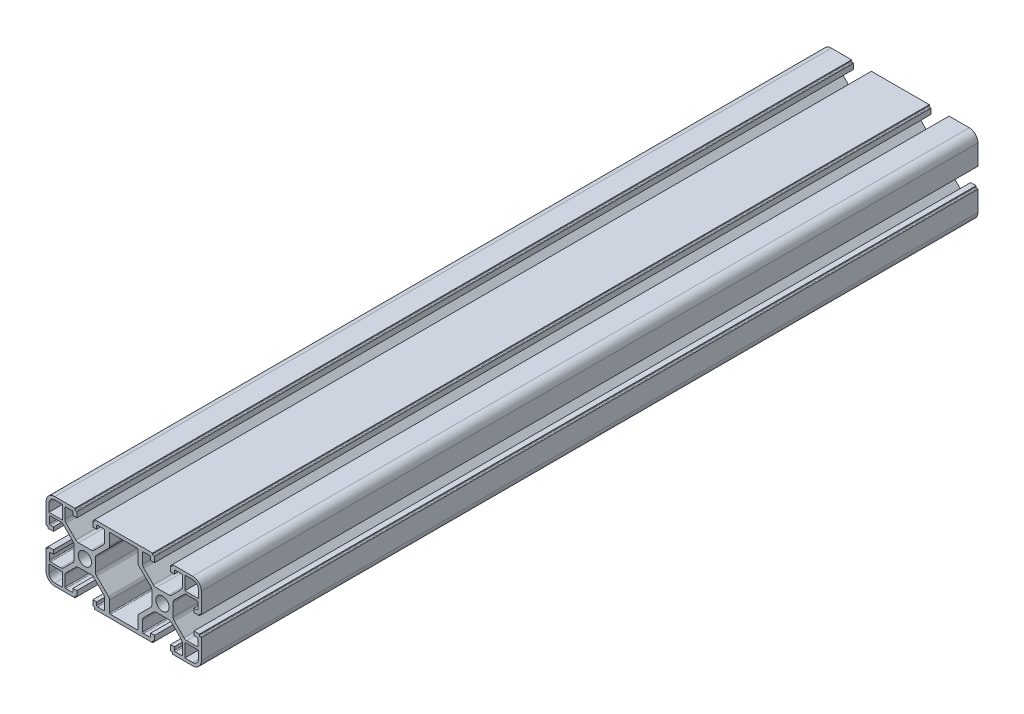
SolidWorks part; units mm, degrees
material "1060 合金"
ref_plane "前视基准面" through (0, 0, 0) normal (0, 0, 1) x (1, 0, 0)
ref_plane "上视基准面" through (0, 0, 0) normal (0, 1, 0) x (1, 0, 0)
ref_plane "右视基准面" through (0, 0, 0) normal (1, 0, 0) x (0, 0, -1)
sketch "草图1" plane through (0, 0, 0) normal (0, 0, 1) x (1, 0, 0)
  line L0 (-18.5, 15.5) -> (-18.5, 11.5)
  line L1 (-3.2574, 5.5) -> (3.2574, 5.5)
  line L2 (-5.5, 3.2574) -> (-5.5, -3.2574)
  line L3 (-3.2574, -5.5) -> (3.2574, -5.5)
  line L4 (5.5, 3.2574) -> (5.5, -3.2574)
  line L5 (-5.5, 5.5) -> (5.5, -5.5) construction
  line L6 (-5.5, -5.5) -> (5.5, 5.5) construction
  line L7 (-15.5, 20) -> (-5.1, 20)
  line L8 (-20, 15.5) -> (-20, 5.1)
  line L9 (-15.5, -20) -> (-5.1, -20)
  line L10 (60, 15.5) -> (60, 5.1)
  line L11 (36.7426, 5.5) -> (43.2574, 5.5)
  line L12 (34.5, 3.2574) -> (34.5, -3.2574)
  line L13 (36.7426, -5.5) -> (43.2574, -5.5)
  line L14 (45.5, 3.2574) -> (45.5, -3.2574)
  line L15 (34.5, 5.5) -> (45.5, -5.5) construction
  line L16 (34.5, -5.5) -> (45.5, 5.5) construction
  line L21 (-11.5, 18.5) -> (-15.5, 18.5)
  line L22 (-18.5, 11.5) -> (-11.5, 11.5)
  line L27 (6.0858, 4.6716) -> (12.1142, 10.7)
  line L28 (4.6716, 6.0858) -> (9.6642, 11.0784)
  line L33 (20, 42.3045) -> (20, -35.7395) construction
  line L34 (58.5, 15.5) -> (58.5, 11.5)
  line L39 (51.5, 18.5) -> (55.5, 18.5)
  line L40 (51.5, 18.5) -> (51.5, 11.5)
  line L41 (-9.6642, 11.0784) -> (-4.6716, 6.0858)
  line L47 (58.5, 11.5) -> (51.5, 11.5)
  line L48 (27.3, 17.7) -> (27.3, 12.1142)
  line L53 (33.9142, 4.6716) -> (27.8858, 10.7)
  line L54 (35.3284, 6.0858) -> (30.3358, 11.0784)
  line L58 (-10.25, 20.75) -> (-10.25, 20) construction
  line L59 (-20.25, 20.25) -> (-10.75, 10.75) construction
  line L60 (-20.25, 10.75) -> (-10.25, 20.75) construction
  line L65 (29.75, 17.7) -> (29.75, 12.4926)
  line L66 (30.25, 18.2) -> (33.4, 18.2)
  line L67 (-11.0784, 9.6642) -> (-6.0858, 4.6716)
  line L68 (33.9, 17.7) -> (33.9, 16.2)
  line L69 (33.9, 16.2) -> (35.9, 16.2)
  line L70 (34.9, 19.5) -> (34.9, 20)
  line L71 (35.9, 19) -> (35.4, 19)
  line L72 (35.9, 16.2) -> (35.9, 19)
  line L73 (51.0784, 9.6642) -> (46.0858, 4.6716)
  line L74 (52.4926, 10.25) -> (57.7, 10.25)
  line L76 (10.25, 17.7) -> (10.25, 12.4926)
  line L79 (12.7, 17.7) -> (12.7, 12.1142)
  line L81 (13.2, 18.2) -> (26.8, 18.2)
  line L83 (45.1, 19.5) -> (45.1, 20)
  line L84 (9.75, 18.2) -> (6.6, 18.2)
  line L85 (6.1, 17.7) -> (6.1, 16.2)
  line L86 (6.1, 16.2) -> (4.1, 16.2)
  line L87 (4.1, 16.2) -> (4.1, 19)
  line L88 (4.1, 19) -> (4.6, 19)
  line L89 (5.1, 19.5) -> (5.1, 20)
  line L90 (0, 23.211) -> (0, -33.1546) construction
  line L91 (-4.1, 16.2) -> (-6.1, 16.2)
  line L92 (-6.1, 16.2) -> (-6.1, 17.7)
  line L93 (-6.6, 18.2) -> (-9.75, 18.2)
  line L94 (-4.1, 16.2) -> (-4.1, 19)
  line L95 (-4.1, 19) -> (-4.656, 19)
  line L96 (-4.656, 19) -> (-4.6, 19)
  line L97 (-5.1, 19.5) -> (-5.1, 20)
  line L98 (-10.25, 17.7) -> (-10.25, 12.4926)
  line L99 (44.1, 19) -> (44.656, 19)
  line L100 (44.1, 16.2) -> (44.1, 19)
  line L101 (-11.5, 18.5) -> (-11.5, 11.5)
  line L102 (-12.4926, 10.25) -> (-17.7, 10.25)
  line L103 (44.1, 16.2) -> (46.1, 16.2)
  line L104 (46.1, 16.2) -> (46.1, 17.7)
  line L105 (46.6, 18.2) -> (49.75, 18.2)
  line L106 (50.25, 17.7) -> (50.25, 12.4926)
  line L107 (49.6642, 11.0784) -> (44.6716, 6.0858)
  line L108 (-37.1629, 0) -> (-20, 0) construction
  line L109 (-11.5, -18.5) -> (-15.5, -18.5)
  line L110 (-11.5, -18.5) -> (-11.5, -11.5)
  line L111 (-18.5, -11.5) -> (-11.5, -11.5)
  line L112 (-18.5, -15.5) -> (-18.5, -11.5)
  line L113 (-10.25, -17.7) -> (-10.25, -12.4926)
  line L114 (-12.4926, -10.25) -> (-17.7, -10.25)
  line L115 (-9.6642, -11.0784) -> (-4.6716, -6.0858)
  line L116 (-11.0784, -9.6642) -> (-6.0858, -4.6716)
  line L117 (-4.1, -16.2) -> (-4.1, -19)
  line L118 (-4.1, -16.2) -> (-6.1, -16.2)
  line L119 (-6.1, -16.2) -> (-6.1, -17.7)
  line L120 (-6.6, -18.2) -> (-9.75, -18.2)
  line L121 (-4.1, -19) -> (-4.656, -19)
  line L122 (-5.1, -19.5) -> (-5.1, -20)
  line L123 (10.25, -17.7) -> (10.25, -12.4926)
  line L124 (12.7, -17.7) -> (12.7, -12.1142)
  line L125 (4.6716, -6.0858) -> (9.6642, -11.0784)
  line L126 (6.0858, -4.6716) -> (12.1142, -10.7)
  line L127 (13.2, -18.2) -> (26.8, -18.2)
  line L128 (5.1, -19.5) -> (5.1, -20)
  line L129 (4.1, -19) -> (4.6, -19)
  line L130 (4.1, -16.2) -> (4.1, -19)
  line L131 (6.1, -16.2) -> (4.1, -16.2)
  line L132 (6.1, -17.7) -> (6.1, -16.2)
  line L133 (9.75, -18.2) -> (6.6, -18.2)
  line L134 (35.3284, -6.0858) -> (30.3358, -11.0784)
  line L135 (34.9, -19.5) -> (34.9, -20)
  line L136 (35.9, -19) -> (35.4, -19)
  line L137 (35.9, -16.2) -> (35.9, -19)
  line L138 (33.9, -16.2) -> (35.9, -16.2)
  line L139 (33.9, -17.7) -> (33.9, -16.2)
  line L140 (30.25, -18.2) -> (33.4, -18.2)
  line L141 (29.75, -17.7) -> (29.75, -12.4926)
  line L142 (33.9142, -4.6716) -> (27.8858, -10.7)
  line L143 (27.3, -17.7) -> (27.3, -12.1142)
  line L144 (52.4926, -10.25) -> (57.7, -10.25)
  line L145 (44.1, -19) -> (44.656, -19)
  line L146 (45.1, -19.5) -> (45.1, -20)
  line L147 (44.1, -16.2) -> (44.1, -19)
  line L148 (44.1, -16.2) -> (46.1, -16.2)
  line L149 (46.1, -16.2) -> (46.1, -17.7)
  line L150 (46.6, -18.2) -> (49.75, -18.2)
  line L151 (50.25, -17.7) -> (50.25, -12.4926)
  line L152 (49.6642, -11.0784) -> (44.6716, -6.0858)
  line L153 (51.0784, -9.6642) -> (46.0858, -4.6716)
  line L154 (58.5, -15.5) -> (58.5, -11.5)
  line L155 (58.5, -11.5) -> (51.5, -11.5)
  line L156 (51.5, -18.5) -> (51.5, -11.5)
  line L157 (51.5, -18.5) -> (55.5, -18.5)
  line L158 (45.1, 20) -> (55.5, 20)
  line L159 (5.1, 20) -> (34.9, 20)
  line L160 (5.1, -20) -> (34.9, -20)
  line L161 (45.1, -20) -> (55.5, -20)
  line L162 (-16.2, 4.1) -> (-16.2, 6.1)
  line L163 (-16.2, 6.1) -> (-17.7, 6.1)
  line L164 (-18.2, 6.6) -> (-18.2, 9.75)
  line L165 (-19.5, 5.1) -> (-20, 5.1)
  line L166 (-19, 4.1) -> (-19, 4.656)
  line L167 (-16.2, 4.1) -> (-19, 4.1)
  line L168 (-18.2, -6.6) -> (-18.2, -9.75)
  line L169 (-16.2, -6.1) -> (-17.7, -6.1)
  line L170 (-16.2, -4.1) -> (-16.2, -6.1)
  line L171 (-16.2, -4.1) -> (-19, -4.1)
  line L172 (-19.5, -5.1) -> (-20, -5.1)
  line L173 (-19, -4.1) -> (-19, -4.656)
  line L174 (59.5, -5.1) -> (60, -5.1)
  line L175 (59, -4.1) -> (59, -4.656)
  line L176 (56.2, -4.1) -> (59, -4.1)
  line L177 (56.2, -4.1) -> (56.2, -6.1)
  line L178 (56.2, -6.1) -> (57.7, -6.1)
  line L179 (58.2, -6.6) -> (58.2, -9.75)
  line L180 (59.5, 5.1) -> (60, 5.1)
  line L181 (59, 4.1) -> (59, 4.656)
  line L182 (56.2, 4.1) -> (59, 4.1)
  line L183 (56.2, 4.1) -> (56.2, 6.1)
  line L184 (56.2, 6.1) -> (57.7, 6.1)
  line L185 (58.2, 6.6) -> (58.2, 9.75)
  line L186 (60, -5.1) -> (60, -15.5)
  line L187 (-20, -5.1) -> (-20, -15.5)
  line L188 (-5.5, 0) -> (60, 0) construction
  circle A0 centre (0, 0) radius 3.4
  circle A1 centre (40, 0) radius 3.4
  arc A2 (-15.5, 20) -> (-20, 15.5) centre (-15.5, 15.5) ccw
  arc A3 (60, 15.5) -> (55.5, 20) centre (55.5, 15.5) ccw
  arc A4 (55.5, -20) -> (60, -15.5) centre (55.5, -15.5) ccw
  arc A5 (-20, -15.5) -> (-15.5, -20) centre (-15.5, -15.5) ccw
  arc A10 (-15.5, 18.5) -> (-18.5, 15.5) centre (-15.5, 15.5) ccw
  arc A11 (-9.75, 18.2) -> (-10.25, 17.7) centre (-9.75, 17.7) ccw
  arc A12 (-6.1, 17.7) -> (-6.6, 18.2) centre (-6.6, 17.7) ccw
  arc A13 (-5.1, 19.5) -> (-4.6, 19) centre (-4.6, 19.5) ccw
  arc A14 (4.6, 19) -> (5.1, 19.5) centre (4.6, 19.5) ccw
  arc A15 (6.6, 18.2) -> (6.1, 17.7) centre (6.6, 17.7) ccw
  arc A16 (10.25, 17.7) -> (9.75, 18.2) centre (9.75, 17.7) ccw
  arc A17 (9.6642, 11.0784) -> (10.25, 12.4926) centre (8.25, 12.4926) ccw
  arc A18 (-10.25, 12.4926) -> (-9.6642, 11.0784) centre (-8.25, 12.4926) ccw
  arc A20 (-11.0784, 9.6642) -> (-12.4926, 10.25) centre (-12.4926, 8.25) ccw
  arc A21 (12.1142, 10.7) -> (12.7, 12.1142) centre (10.7, 12.1142) ccw
  arc A22 (-4.6716, 6.0858) -> (-3.2574, 5.5) centre (-3.2574, 7.5) ccw
  arc A23 (3.2574, 5.5) -> (4.6716, 6.0858) centre (3.2574, 7.5) ccw
  arc A24 (13.2, 18.2) -> (12.7, 17.7) centre (13.2, 17.7) ccw
  arc A25 (6.0858, 4.6716) -> (5.5, 3.2574) centre (7.5, 3.2574) ccw
  arc A26 (-5.5, 3.2574) -> (-6.0858, 4.6716) centre (-7.5, 3.2574) ccw
  arc A27 (58.5, 15.5) -> (55.5, 18.5) centre (55.5, 15.5) ccw
  arc A28 (26.8, 18.2) -> (27.3, 17.7) centre (26.8, 17.7) cw
  arc A29 (27.8858, 10.7) -> (27.3, 12.1142) centre (29.3, 12.1142) cw
  arc A30 (33.9142, 4.6716) -> (34.5, 3.2574) centre (32.5, 3.2574) cw
  arc A31 (36.7426, 5.5) -> (35.3284, 6.0858) centre (36.7426, 7.5) cw
  arc A32 (30.3358, 11.0784) -> (29.75, 12.4926) centre (31.75, 12.4926) cw
  arc A33 (29.75, 17.7) -> (30.25, 18.2) centre (30.25, 17.7) cw
  arc A34 (33.4, 18.2) -> (33.9, 17.7) centre (33.4, 17.7) cw
  arc A35 (35.4, 19) -> (34.9, 19.5) centre (35.4, 19.5) cw
  arc A36 (45.5, 3.2574) -> (46.0858, 4.6716) centre (47.5, 3.2574) cw
  arc A37 (44.6716, 6.0858) -> (43.2574, 5.5) centre (43.2574, 7.5) cw
  arc A38 (51.0784, 9.6642) -> (52.4926, 10.25) centre (52.4926, 8.25) cw
  arc A39 (45.1, 19.5) -> (44.6, 19) centre (44.6, 19.5) cw
  arc A40 (46.1, 17.7) -> (46.6, 18.2) centre (46.6, 17.7) cw
  arc A41 (49.75, 18.2) -> (50.25, 17.7) centre (49.75, 17.7) cw
  arc A42 (50.25, 12.4926) -> (49.6642, 11.0784) centre (48.25, 12.4926) cw
  arc A43 (-18.5, -15.5) -> (-15.5, -18.5) centre (-15.5, -15.5) ccw
  arc A44 (-11.0784, -9.6642) -> (-12.4926, -10.25) centre (-12.4926, -8.25) cw
  arc A45 (-10.25, -12.4926) -> (-9.6642, -11.0784) centre (-8.25, -12.4926) cw
  arc A46 (-4.6716, -6.0858) -> (-3.2574, -5.5) centre (-3.2574, -7.5) cw
  arc A47 (-5.5, -3.2574) -> (-6.0858, -4.6716) centre (-7.5, -3.2574) cw
  arc A48 (-6.1, -17.7) -> (-6.6, -18.2) centre (-6.6, -17.7) cw
  arc A49 (-9.75, -18.2) -> (-10.25, -17.7) centre (-9.75, -17.7) cw
  arc A50 (-5.1, -19.5) -> (-4.6, -19) centre (-4.6, -19.5) cw
  arc A51 (12.1142, -10.7) -> (12.7, -12.1142) centre (10.7, -12.1142) cw
  arc A52 (9.6642, -11.0784) -> (10.25, -12.4926) centre (8.25, -12.4926) cw
  arc A53 (6.0858, -4.6716) -> (5.5, -3.2574) centre (7.5, -3.2574) cw
  arc A54 (3.2574, -5.5) -> (4.6716, -6.0858) centre (3.2574, -7.5) cw
  arc A55 (4.6, -19) -> (5.1, -19.5) centre (4.6, -19.5) cw
  arc A56 (6.6, -18.2) -> (6.1, -17.7) centre (6.6, -17.7) cw
  arc A57 (13.2, -18.2) -> (12.7, -17.7) centre (13.2, -17.7) cw
  arc A58 (10.25, -17.7) -> (9.75, -18.2) centre (9.75, -17.7) cw
  arc A59 (33.9142, -4.6716) -> (34.5, -3.2574) centre (32.5, -3.2574) ccw
  arc A60 (36.7426, -5.5) -> (35.3284, -6.0858) centre (36.7426, -7.5) ccw
  arc A61 (35.4, -19) -> (34.9, -19.5) centre (35.4, -19.5) ccw
  arc A62 (33.4, -18.2) -> (33.9, -17.7) centre (33.4, -17.7) ccw
  arc A63 (29.75, -17.7) -> (30.25, -18.2) centre (30.25, -17.7) ccw
  arc A64 (30.3358, -11.0784) -> (29.75, -12.4926) centre (31.75, -12.4926) ccw
  arc A65 (27.8858, -10.7) -> (27.3, -12.1142) centre (29.3, -12.1142) ccw
  arc A66 (26.8, -18.2) -> (27.3, -17.7) centre (26.8, -17.7) ccw
  arc A67 (51.0784, -9.6642) -> (52.4926, -10.25) centre (52.4926, -8.25) ccw
  arc A68 (45.1, -19.5) -> (44.6, -19) centre (44.6, -19.5) ccw
  arc A69 (46.1, -17.7) -> (46.6, -18.2) centre (46.6, -17.7) ccw
  arc A70 (49.75, -18.2) -> (50.25, -17.7) centre (49.75, -17.7) ccw
  arc A71 (50.25, -12.4926) -> (49.6642, -11.0784) centre (48.25, -12.4926) ccw
  arc A72 (45.5, -3.2574) -> (46.0858, -4.6716) centre (47.5, -3.2574) ccw
  arc A73 (44.6716, -6.0858) -> (43.2574, -5.5) centre (43.2574, -7.5) ccw
  arc A74 (55.5, -18.5) -> (58.5, -15.5) centre (55.5, -15.5) ccw
  arc A75 (-17.7, 6.1) -> (-18.2, 6.6) centre (-17.7, 6.6) cw
  arc A76 (-18.2, 9.75) -> (-17.7, 10.25) centre (-17.7, 9.75) cw
  arc A77 (-19.5, 5.1) -> (-19, 4.6) centre (-19.5, 4.6) cw
  arc A78 (-18.2, -9.75) -> (-17.7, -10.25) centre (-17.7, -9.75) ccw
  arc A79 (-17.7, -6.1) -> (-18.2, -6.6) centre (-17.7, -6.6) ccw
  arc A80 (-19.5, -5.1) -> (-19, -4.6) centre (-19.5, -4.6) ccw
  arc A81 (59.5, -5.1) -> (59, -4.6) centre (59.5, -4.6) cw
  arc A82 (57.7, -6.1) -> (58.2, -6.6) centre (57.7, -6.6) cw
  arc A83 (58.2, -9.75) -> (57.7, -10.25) centre (57.7, -9.75) cw
  arc A84 (59.5, 5.1) -> (59, 4.6) centre (59.5, 4.6) ccw
  arc A85 (57.7, 6.1) -> (58.2, 6.6) centre (57.7, 6.6) ccw
  arc A86 (58.2, 9.75) -> (57.7, 10.25) centre (57.7, 9.75) ccw
  point P104 (-4.628, 19)
  point P306 (-20, -5.1)
  dimension "D1" = 6.8
  dimension "D8" = 6.8
  dimension "D13" = 9
  dimension "D14" = 9
  dimension "D15" = 9
  dimension "D16" = 9
  dimension "D17" = 7
  dimension "D18" = 23.2574
  dimension "D19" = 40
  dimension "D20" = 1
  dimension "D65" = 1.5
  dimension "D66" = 6
  dimension "D23" = 1
  dimension "D24" = 1
  dimension "D25" = 1
  dimension "D27" = 1
  dimension "D30" = 1
  dimension "D31" = 4
  dimension "D32" = 4
  dimension "D33" = 2
  dimension "D34" = 4
  dimension "D41" = 4
  dimension "D42" = 4
  dimension "D43" = 1
  dimension "D38" = 4
  dimension "D39" = 4
  dimension "D47" = 15.3284
  dimension "D2" = 5.5
  dimension "D3" = 5.5
  dimension "D4" = 20
  dimension "D5" = 20
  dimension "D7" = 5.5
  dimension "D9" = 10.3358
  dimension "D12" = 20
  dimension "D21" = 7
  dimension "D22" = 7
  dimension "D26" = 1
  dimension "D28" = 1.5
  dimension "D29" = 10.25
  dimension "D35" = 7.5074
  dimension "D36" = 1
  dimension "D37" = 1
  dimension "D40" = 7.5074
  dimension "D44" = 20.5
  dimension "D45" = 15.3284
  dimension "D46" = 2.45
  dimension "D48" = 1.8
  dimension "D51" = 1.8
  dimension "D52" = 4.1
  dimension "D53" = 5.1
  dimension "D56" = 4.1
  dimension "D57" = 1.8
  dimension "D58" = 5.1
  dimension "D59" = 1
  dimension "D60" = 2
  dimension "D61" = 2
  dimension "D62" = 2
extrude "凸台-拉伸1" add sketch "草图1" along normal blind 400
